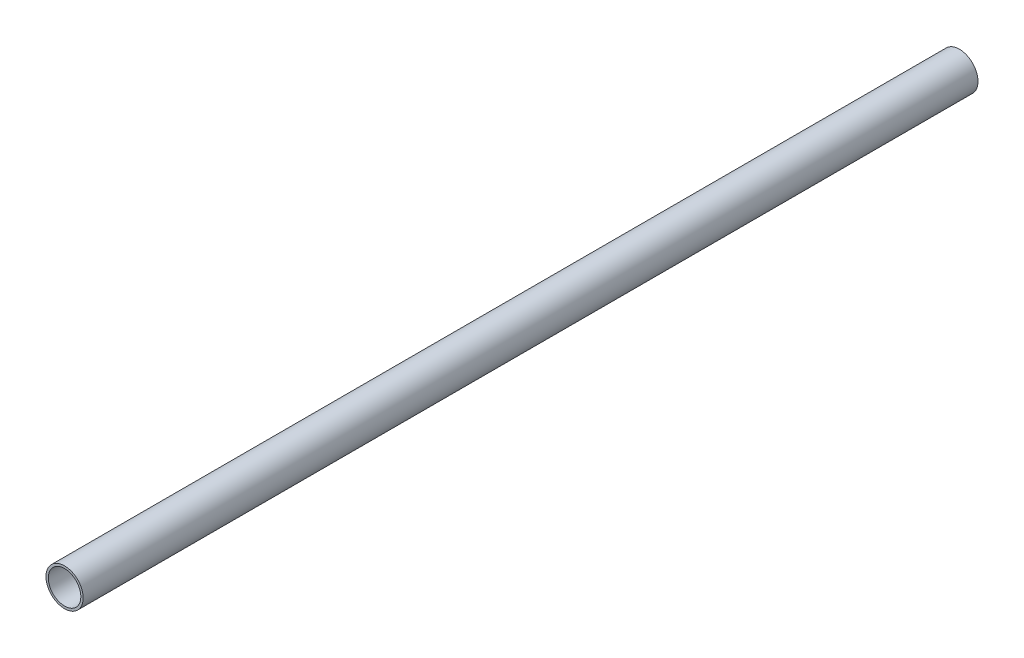
SolidWorks part; units mm, degrees
material "Thornel Mat VMA"
ref_plane "前视基准面" through (0, 0, 0) normal (0, 0, 1) x (1, 0, 0)
ref_plane "上视基准面" through (0, 0, 0) normal (0, 1, 0) x (1, 0, 0)
ref_plane "右视基准面" through (0, 0, 0) normal (1, 0, 0) x (0, 0, -1)
sketch "草图1" plane through (0, 0, 0) normal (0, 0, 1) x (1, 0, 0)
  circle A0 centre (0, 0) radius 8
  circle A1 centre (0, 0) radius 7
  dimension "D1" = 16
  dimension "D2" = 14
extrude "凸台-拉伸1" add sketch "草图1" along normal mid plane 385
